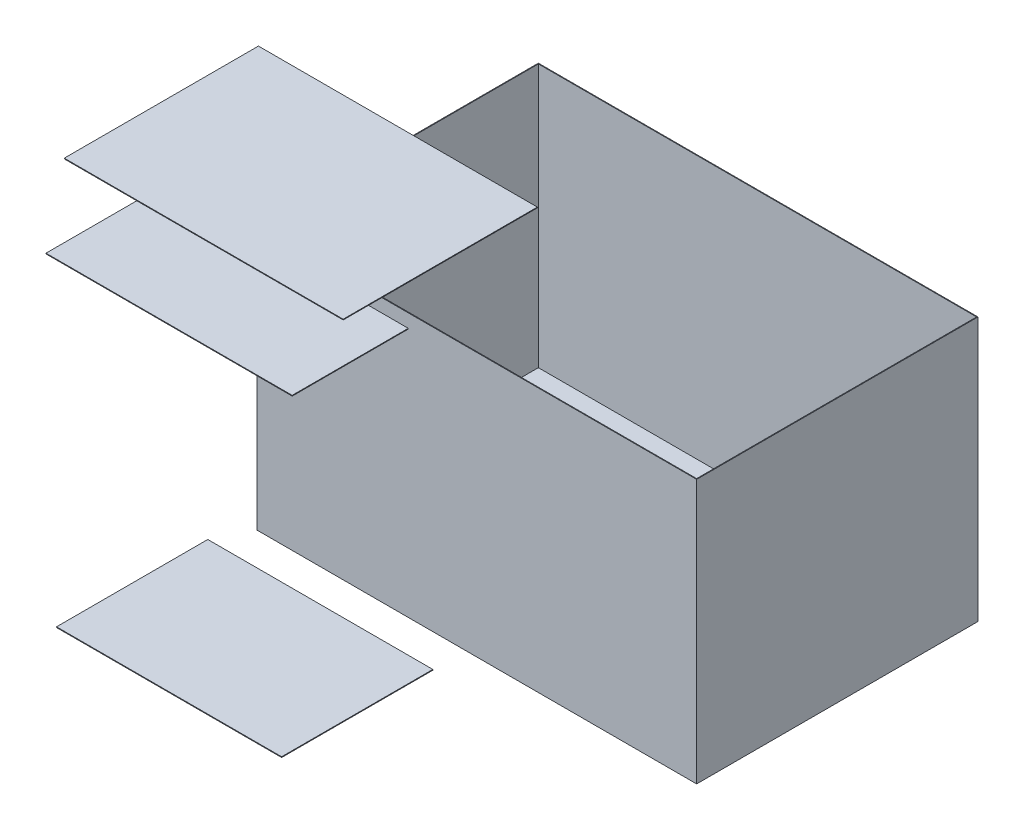
SolidWorks part; units mm, degrees
ref_plane "Спереди" through (0, 0, 0) normal (0, 0, 1) x (1, 0, 0)
ref_plane "Сверху" through (0, 0, 0) normal (0, 1, 0) x (1, 0, 0)
ref_plane "Справа" through (0, 0, 0) normal (1, 0, 0) x (0, 0, -1)
sketch "MASTER_FOOTPRINT" plane through (0, 0, 0) normal (0, 1, 0) x (1, 0, 0)
  line L1 (0, 0) -> (1250, 0)
  line L2 (0, 0) -> (0, 800)
  line L3 (0, 800) -> (1250, 800)
  line L4 (1250, 0) -> (1250, 800)
  dimension "D1" = 1250
  dimension "D2" = 800
extrude "BATH_BASE_PLATE" add sketch "MASTER_FOOTPRINT" along normal blind 750
shell "BATH_SHELL_2MM" thickness 2
sketch "Эскиз1" plane through (0, 0, 0) normal (0, 1, 0) x (1, 0, 0)
  line L1 (80, -220) -> (720, -220)
  line L2 (80, -220) -> (80, -650)
  line L3 (80, -650) -> (720, -650)
  line L4 (720, -220) -> (720, -650)
extrude "INLET_IMPACT_BAFFLE" add sketch "Эскиз1" along normal blind 2 from offset 125 separate body
sketch "Эскиз2" plane through (0, 0, 0) normal (0, 1, 0) x (1, 0, 0)
  line L0 (2, 2) -> (1248, 2) construction
  line L1 (30, 2) -> (770, 2)
  line L2 (30, 2) -> (30, -650)
  line L3 (30, -650) -> (770, -650)
  line L4 (770, 2) -> (770, -650)
  line L5 (80, -220) -> (80, -650) construction
  circle A0 centre (49.4737, -125) radius 11
  circle A1 centre (88.4211, -125) radius 11
  circle A2 centre (80, -239) radius 8.4211
  circle A3 centre (80, -267.5) radius 8.4211
  circle A4 centre (80, -296) radius 8.4211
  circle A5 centre (80, -324.5) radius 8.4211
  circle A6 centre (80, -353) radius 8.4211
  circle A7 centre (80, -381.5) radius 8.4211
  circle A8 centre (80, -410) radius 8.4211
  circle A9 centre (80, -435) radius 9.1194
  circle A10 centre (80, -467) radius 8.4211
  circle A11 centre (80, -495.5) radius 8.4211
  circle A12 centre (80, -524) radius 8.4211
  circle A13 centre (127.3684, -125) radius 11
  circle A14 centre (166.3158, -125) radius 11
  circle A15 centre (205.2632, -125) radius 11
  circle A16 centre (244.2105, -125) radius 11
  circle A17 centre (283.1579, -125) radius 11
  circle A18 centre (322.1053, -125) radius 11
  circle A19 centre (361.0526, -125) radius 11
  circle A20 centre (400, -125) radius 11
  circle A21 centre (438.9474, -125) radius 11
  circle A22 centre (477.8947, -125) radius 11
  circle A23 centre (516.8421, -125) radius 11
  circle A24 centre (555.7895, -125) radius 11
  circle A25 centre (594.7368, -125) radius 11
  circle A26 centre (633.6842, -125) radius 11
  circle A27 centre (672.6316, -125) radius 11
  circle A28 centre (711.5789, -125) radius 11
  circle A29 centre (711.5789, -239) radius 8.4211
  circle A30 centre (711.5789, -267.5) radius 8.4211
  circle A31 centre (711.5789, -296) radius 8.4211
  circle A32 centre (711.5789, -324.5) radius 8.4211
  circle A33 centre (711.5789, -353) radius 8.4211
  circle A34 centre (711.5789, -381.5) radius 8.4211
  circle A35 centre (711.5789, -410) radius 8.4211
  circle A36 centre (711.5789, -435) radius 8.4211
  circle A37 centre (711.5789, -467) radius 8.4211
  circle A38 centre (711.5789, -495.5) radius 8.4211
  circle A39 centre (711.5789, -524) radius 8.4211
  circle A40 centre (750.5263, -125) radius 19.4737
  circle A41 centre (750.5263, -144.4737) radius 19.4737
  circle A42 centre (750.5263, -210.5) radius 19.4737
  circle A43 centre (750.5263, -229.9737) radius 19.4737
  circle A44 centre (750.5263, -296) radius 19.4737
  circle A45 centre (750.5263, -315.4737) radius 19.4737
  circle A46 centre (750.5263, -353) radius 19.4737
  circle A47 centre (750.5263, -372.4737) radius 19.4737
  circle A48 centre (750.5263, -435) radius 19.4737
  circle A49 centre (750.5263, -454.4737) radius 19.4737
  circle A50 centre (750.5263, -524) radius 19.4737
sketch "Эскиз3" plane through (0, 0, 0) normal (0, 1, 0) x (1, 0, 0)
  line L0 (30, -650) -> (770, -650) construction
  line L1 (50, -320) -> (750, -320)
  line L2 (50, -320) -> (50, -650)
  line L3 (50, -650) -> (750, -650)
  line L4 (750, -320) -> (750, -650)
extrude "OUTLET_SUBMERGED_BAFFLE" add sketch "Эскиз3" along normal blind 2 from offset 1030 separate body
sketch "Эскиз4" plane through (0, 0, 0) normal (0, 1, 0) x (1, 0, 0)
  line L1 (2, 2) -> (795, 2)
  line L2 (2, 2) -> (2, -550)
  line L3 (2, -550) -> (795, -550)
  line L4 (795, 2) -> (795, -550)
extrude "OVERFLOW_WEIR_Z550" add sketch "Эскиз4" along normal blind 2 from offset 1190 separate body
equation "\"AI_Q_Peak\"= 0.006"
equation "\"AI_B_Bath\" = 800"
equation "\"AI_L_Settle\" = 800"
equation "\"AI_L_Inlet\"= 250"
equation "\"AI_L_Outlet\"= 200"
equation "\"AI_L_Bath\" = 1250"
equation "\"AI_H_Water\"= 550"
equation "\"AI_H_Freeboard\"= 200"
equation "\"AI_H_Bath\"= 750"
equation "\"AI_Shell_Thickness\"= 2"
equation "\"AI_Inlet_DN\"= 100"
equation "\"AI_Weir_Width\"= 600"
equation "\"AI_Inlet_Baffle_Offset\"= 125"
equation "\"AI_Distributor_Open_Area\"= 0.28"
equation "\"AI_Distributor_Hole_Dia\"= 22"
equation "\"AI_Distributor_Blind_Zone\"= 110"
equation "\"AI_Outlet_Baffle_Depth\"= 250"
equation "\"AI_Screw_Diameter\"= 100"
equation "\"AI_Screw_Pitch\"= 100"
equation "\"AI_Screw_Angle\"= 30"
equation "\"AI_Screw_Rpm\"= 15"
equation "\"AI_Screw_Clearance\"= 5"
equation "\"AI_Liner_Thickness\"= 5"
equation "\"AI_Discharge_Height\"= 650"
equation "\"AI_Frame_Height\"= 500"
equation "\"D1@MASTER_FOOTPRINT\" = \"AI_L_Bath\""
equation "\"D2@MASTER_FOOTPRINT\" = \"AI_B_Bath\""
equation "\"D1@BATH_BASE_PLATE\" = \"AI_H_Bath\""
